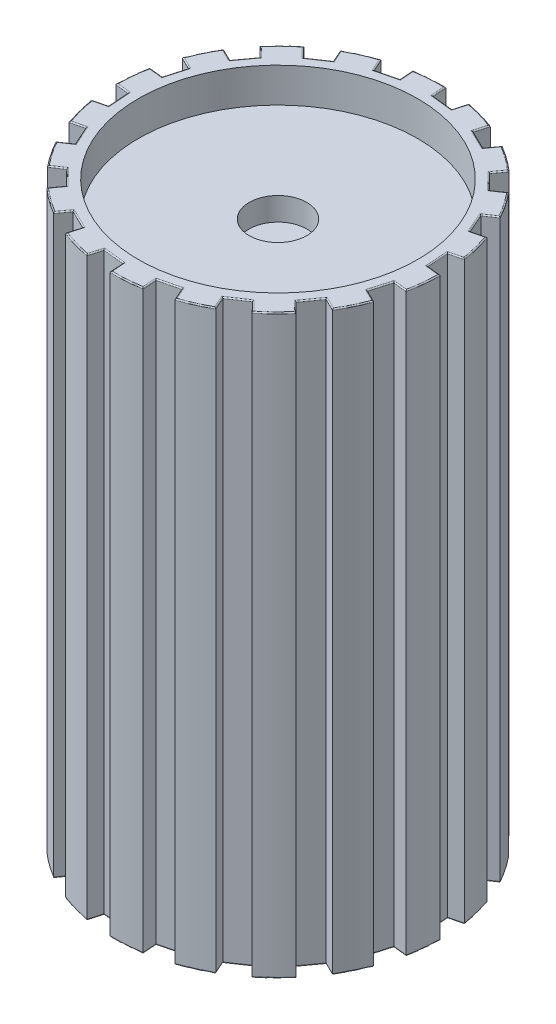
SolidWorks part; units mm, degrees
ref_plane "Front Plane" through (0, 0, 0) normal (0, 0, 1) x (1, 0, 0)
ref_plane "Top Plane" through (0, 0, 0) normal (0, 1, 0) x (1, 0, 0)
ref_plane "Right Plane" through (0, 0, 0) normal (1, 0, 0) x (0, 0, -1)
other "Configuration Table"
sketch "草图1" plane through (0, 0, 0) normal (0, 1, 0) x (1, 0, 0)
  circle A0 centre (0, 0) radius 13
  dimension "D1" = 26
extrude "凸台-拉伸1" add sketch "草图1" along normal blind 50
sketch "草图6" plane through (0, 50, 0) normal (0, 1, 0) x (1, 0, 0)
  circle A0 centre (0, 0) radius 14.2
  dimension "D1" = 28.4
extrude "凸台-拉伸4" add sketch "草图6" against normal through all
sketch "草图2" plane through (0, 50, 0) normal (0, 1, 0) x (1, 0, 0)
  circle A0 centre (0, 0) radius 12
  dimension "D1" = 24
extrude "切除-拉伸1" cut sketch "草图2" against normal blind 3
sketch "草图7" plane through (0, 50, 0) normal (0, 1, 0) x (1, 0, 0)
  line L0 (-14.206, 5.4386) -> (-12.2092, 4.4648)
  line L1 (-14.206, 5.4386) -> (-14.9294, 2.9159)
  line L2 (-12.2092, 4.4648) -> (-12.72, 2.6836)
  line L3 (-14.9294, 2.9159) -> (-12.72, 2.6836)
  line L4 (-15.2094, 0.2519) -> (-13, 0.0197)
  line L5 (-15.2094, 0.2519) -> (-15.0263, -2.3661)
  line L6 (-15.0263, -2.3661) -> (-12.8707, -1.8287)
  line L7 (-13, 0.0197) -> (-12.8707, -1.8287)
  line L8 (-14.3783, -4.9652) -> (-12.2227, -4.4277)
  line L9 (-14.3783, -4.9652) -> (-13.3108, -7.3627)
  line L10 (-13.3108, -7.3627) -> (-11.4691, -6.1205)
  line L11 (-12.2227, -4.4277) -> (-11.4691, -6.1205)
  line L12 (-11.813, -9.5834) -> (-9.9712, -8.3411)
  line L13 (-11.813, -9.5834) -> (-9.9899, -11.4713)
  line L14 (-9.9899, -11.4713) -> (-8.6841, -9.674)
  line L15 (-9.9712, -8.3411) -> (-8.6841, -9.674)
  line L16 (-7.8229, -13.0457) -> (-6.5171, -11.2485)
  line L17 (-7.8229, -13.0457) -> (-5.464, -14.1962)
  line L18 (-5.464, -14.1962) -> (-4.8517, -12.0607)
  line L19 (-6.5171, -11.2485) -> (-4.8517, -12.0607)
  line L20 (-2.8892, -14.9345) -> (-2.2768, -12.7991)
  line L21 (-2.8892, -14.9345) -> (-0.2791, -15.2089)
  line L22 (-0.2791, -15.2089) -> (-0.4341, -12.9928)
  line L23 (-2.2768, -12.7991) -> (-0.4341, -12.9928)
  line L24 (2.393, -15.022) -> (2.238, -12.8059)
  line L25 (2.393, -15.022) -> (4.9395, -14.3871)
  line L26 (4.9395, -14.3871) -> (4.0359, -12.3577)
  line L27 (2.238, -12.8059) -> (4.0359, -12.3577)
  line L28 (7.3865, -13.2977) -> (6.4829, -11.2682)
  line L29 (7.3865, -13.2977) -> (9.5623, -11.8301)
  line L30 (9.5623, -11.8301) -> (8.0191, -10.232)
  line L31 (6.4829, -11.2682) -> (8.0191, -10.232)
  line L32 (11.4891, -9.9694) -> (9.9459, -8.3713)
  line L33 (11.4891, -9.9694) -> (13.0317, -7.8462)
  line L34 (13.0317, -7.8462) -> (11.035, -6.8723)
  line L35 (9.9459, -8.3713) -> (11.035, -6.8723)
  line L36 (14.206, -5.4386) -> (12.2092, -4.4648)
  line L37 (14.206, -5.4386) -> (14.9294, -2.9159)
  line L38 (14.9294, -2.9159) -> (12.72, -2.6836)
  line L39 (12.2092, -4.4648) -> (12.72, -2.6836)
  line L40 (15.2094, -0.2519) -> (13, -0.0197)
  line L41 (15.2094, -0.2519) -> (15.0263, 2.3661)
  line L42 (15.0263, 2.3661) -> (12.8707, 1.8287)
  line L43 (13, -0.0197) -> (12.8707, 1.8287)
  line L44 (14.3783, 4.9652) -> (12.2227, 4.4277)
  line L45 (14.3783, 4.9652) -> (13.3108, 7.3627)
  line L46 (13.3108, 7.3627) -> (11.4691, 6.1205)
  line L47 (12.2227, 4.4277) -> (11.4691, 6.1205)
  line L48 (11.813, 9.5834) -> (9.9712, 8.3411)
  line L49 (11.813, 9.5834) -> (9.9899, 11.4713)
  line L50 (9.9899, 11.4713) -> (8.6841, 9.674)
  line L51 (9.9712, 8.3411) -> (8.6841, 9.674)
  line L52 (7.8229, 13.0457) -> (6.5171, 11.2485)
  line L53 (7.8229, 13.0457) -> (5.464, 14.1962)
  line L54 (5.464, 14.1962) -> (4.8517, 12.0607)
  line L55 (6.5171, 11.2485) -> (4.8517, 12.0607)
  line L56 (2.8892, 14.9345) -> (2.2768, 12.7991)
  line L57 (2.8892, 14.9345) -> (0.2791, 15.2089)
  line L58 (0.2791, 15.2089) -> (0.4341, 12.9928)
  line L59 (2.2768, 12.7991) -> (0.4341, 12.9928)
  line L60 (-2.393, 15.022) -> (-2.238, 12.8059)
  line L61 (-2.393, 15.022) -> (-4.9395, 14.3871)
  line L62 (-4.9395, 14.3871) -> (-4.0359, 12.3577)
  line L63 (-2.238, 12.8059) -> (-4.0359, 12.3577)
  line L64 (-7.3865, 13.2977) -> (-6.4829, 11.2682)
  line L65 (-7.3865, 13.2977) -> (-9.5623, 11.8301)
  line L66 (-9.5623, 11.8301) -> (-8.0191, 10.232)
  line L67 (-6.4829, 11.2682) -> (-8.0191, 10.232)
  line L68 (-11.4891, 9.9694) -> (-9.9459, 8.3713)
  line L69 (-11.4891, 9.9694) -> (-13.0317, 7.8462)
  line L70 (-13.0317, 7.8462) -> (-11.035, 6.8723)
  line L71 (-9.9459, 8.3713) -> (-11.035, 6.8723)
  circle A0 centre (0, 0) radius 13 construction
  point P78 (0, 0)
  point P150 (0, 0)
  dimension "D1" = 26
  dimension "D2" = 100
  dimension "D3" = 100
  dimension "D4" = 18
extrude "切除-拉伸2" cut sketch "草图7" against normal through all
sketch "草图8" plane through (0, 47, 0) normal (0, 1, 0) x (1, 0, 0)
  circle A0 centre (0, 0) radius 2.5
  dimension "D1" = 5
extrude "切除-拉伸3" cut sketch "草图8" against normal blind 2
fillet "圆角6" radius 0.1 72 edges at (-13.3196, 0, -2.7467) (-12.4646, 0, -3.5742) (-12.7512, 0, -4.7291) (-8.4379, 0, -10.6658) (-9.8641, 0, -10.2147) (-10.3647, 0, -8.805) (-10.4905, 0, -7.6218) (-11.5769, 0, -7.1366) (-12.7629, 0, -6.2249) (-14.1222, 0, -1.4843) (-13.5996, 0, -0.0827) (-12.9354, 0, 0.9045) (-13.4558, 0, 1.9746) (-13.7782, 0, 3.4353) (-12.8078, 0, 4.5736) (-11.8459, 0, 5.2741) (-11.9689, 0, 6.4576) (-11.7724, 0, 7.9405) (-10.4711, 0, 8.6783) (-9.3277, 0, 9.0076) (-9.0385, 0, 10.1618) (-8.3466, 0, 11.488) (-6.8715, 0, 11.7362) (-5.6844, 0, 11.6546) (-5.0179, 0, 12.6403) (-3.9141, 0, 13.6499) (-2.443, 0, 13.3786) (-1.3555, 0, 12.8959) (-0.392, 0, 13.5942) (0.9905, 0, 14.1654) (2.2801, 0, 13.4074) (3.137, 0, 12.5818) (4.2811, 0, 12.9085) (5.7756, 0, 12.9724) (6.7282, 0, 11.819) (7.251, 0, 10.7501) (8.4379, 0, 10.6658) (9.8641, 0, 10.2147) (10.3647, 0, 8.805) (10.4905, 0, 7.6218) (11.5769, 0, 7.1366) (12.7629, 0, 6.2249) (12.7512, 0, 4.7291) (12.4646, 0, 3.5742) (13.3196, 0, 2.7467) (14.1222, 0, 1.4843) (13.5996, 0, 0.0827) (12.9354, 0, -0.9045) (13.4558, 0, -1.9746) (13.7782, 0, -3.4353) (12.8078, 0, -4.5736) (11.8459, 0, -5.2741) (11.9689, 0, -6.4576) (11.7724, 0, -7.9405) (10.4711, 0, -8.6783) (9.3277, 0, -9.0076) (9.0385, 0, -10.1618) (8.3466, 0, -11.488) (6.8715, 0, -11.7362) (5.6844, 0, -11.6546) (5.0179, 0, -12.6403) (3.9141, 0, -13.6499) (2.443, 0, -13.3786) (1.3555, 0, -12.8959) (0.392, 0, -13.5942) (-0.9905, 0, -14.1654) (-2.2801, 0, -13.4074) (-3.137, 0, -12.5818) (-4.2811, 0, -12.9085) (-5.7756, 0, -12.9724) (-6.7282, 0, -11.819) (-7.251, 0, -10.7501)
fillet "圆角7" radius 0.1 73 edges at (0, 50, 12) (-12.7512, 50, -4.7291) (-12.4646, 50, -3.5742) (-13.3196, 50, -2.7467) (-5.7756, 50, -12.9724) (-4.2811, 50, -12.9085) (-3.137, 50, -12.5818) (-2.2801, 50, -13.4074) (-0.9905, 50, -14.1654) (0.392, 50, -13.5942) (1.3555, 50, -12.8959) (2.443, 50, -13.3786) (3.9141, 50, -13.6499) (5.0179, 50, -12.6403) (5.6844, 50, -11.6546) (6.8715, 50, -11.7362) (8.3466, 50, -11.488) (9.0385, 50, -10.1618) (9.3277, 50, -9.0076) (10.4711, 50, -8.6783) (11.7724, 50, -7.9405) (11.9689, 50, -6.4576) (11.8459, 50, -5.2741) (12.8078, 50, -4.5736) (13.7782, 50, -3.4353) (13.4558, 50, -1.9746) (12.9354, 50, -0.9045) (13.5996, 50, 0.0827) (14.1222, 50, 1.4843) (13.3196, 50, 2.7467) (12.4646, 50, 3.5742) (12.7512, 50, 4.7291) (12.7629, 50, 6.2249) (11.5769, 50, 7.1366) (10.4905, 50, 7.6218) (10.3647, 50, 8.805) (9.8641, 50, 10.2147) (8.4379, 50, 10.6658) (7.251, 50, 10.7501) (6.7282, 50, 11.819) (5.7756, 50, 12.9724) (4.2811, 50, 12.9085) (3.137, 50, 12.5818) (2.2801, 50, 13.4074) (0.9905, 50, 14.1654) (-0.392, 50, 13.5942) (-1.3555, 50, 12.8959) (-2.443, 50, 13.3786) (-3.9141, 50, 13.6499) (-5.0179, 50, 12.6403) (-5.6844, 50, 11.6546) (-6.8715, 50, 11.7362) (-8.3466, 50, 11.488) (-9.0385, 50, 10.1618) (-9.3277, 50, 9.0076) (-10.4711, 50, 8.6783) (-11.7724, 50, 7.9405) (-11.9689, 50, 6.4576) (-11.8459, 50, 5.2741) (-12.8078, 50, 4.5736) (-13.7782, 50, 3.4353) (-13.4558, 50, 1.9746) (-12.9354, 50, 0.9045) (-13.5996, 50, -0.0827) (-14.1222, 50, -1.4843) (-12.7629, 50, -6.2249) (-11.5769, 50, -7.1366) (-10.4905, 50, -7.6218) (-10.3647, 50, -8.805) (-9.8641, 50, -10.2147) (-8.4379, 50, -10.6658) (-7.251, 50, -10.7501) (-6.7282, 50, -11.819)
sketch "草图9" plane through (0, 47, 0) normal (0, 1, 0) x (1, 0, 0)
  circle A0 centre (0, 0) radius 12.1
  circle A1 centre (0, 0) radius 12 construction
  dimension "D1" = 0.1
  dimension "D2" = 24.2
extrude "切除-拉伸4" cut sketch "草图9" along normal through all
